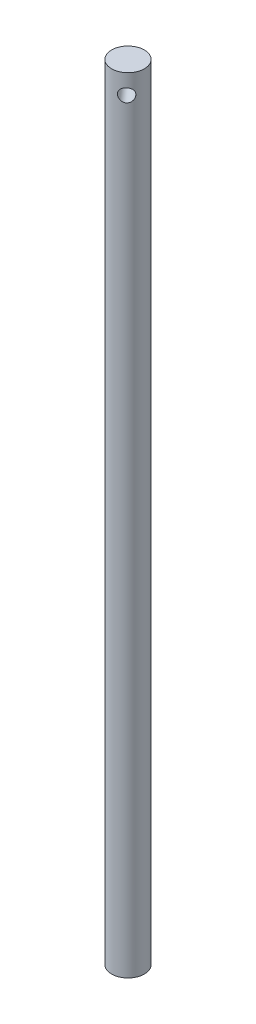
SolidWorks part; units mm, degrees
ref_plane "Front Plane" through (0, 0, 0) normal (0, 0, 1) x (1, 0, 0)
ref_plane "Top Plane" through (0, 0, 0) normal (0, 1, 0) x (1, 0, 0)
ref_plane "Right Plane" through (0, 0, 0) normal (1, 0, 0) x (0, 0, -1)
sketch "Sketch1" plane through (0, 0, 0) normal (0, 1, 0) x (1, 0, 0)
  circle A0 centre (0, 0) radius 12.5
  dimension "D1" = 25
extrude "Boss-Extrude1" add sketch "Sketch1" along normal blind 600
sketch "Sketch4" plane through (0, 600, 0) normal (0, 1, 0) x (1, 0, 0)
  line L0 (0, 0) -> (0.2528, -12.4974)
  line L1 (0.2528, -12.4974) -> (0, 0)
  line L2 (0, 0) -> (8.2665, -9.3763)
  circle A0 centre (0, 0) radius 12.5 construction
ref_plane "Plane1" through (8.2665, 600, 9.3763) normal (0.6613, 0, 0.7501) x (0.7501, 0, -0.6613)
sketch "Sketch5" plane through (8.2665, 600, 9.3763) normal (0.6613, 0, 0.7501) x (0.7501, 0, -0.6613)
  line L0 (0, 0) -> (-8.0752, 0) construction
  circle A0 centre (0, -15) radius 5
  dimension "D1" = 15
extrude "Cut-Extrude2" cut sketch "Sketch5" against normal blind 685 contours A0
chamfer "Chamfer1" distance 2 angle 30 1 edges at (0, 0, 12.5)
